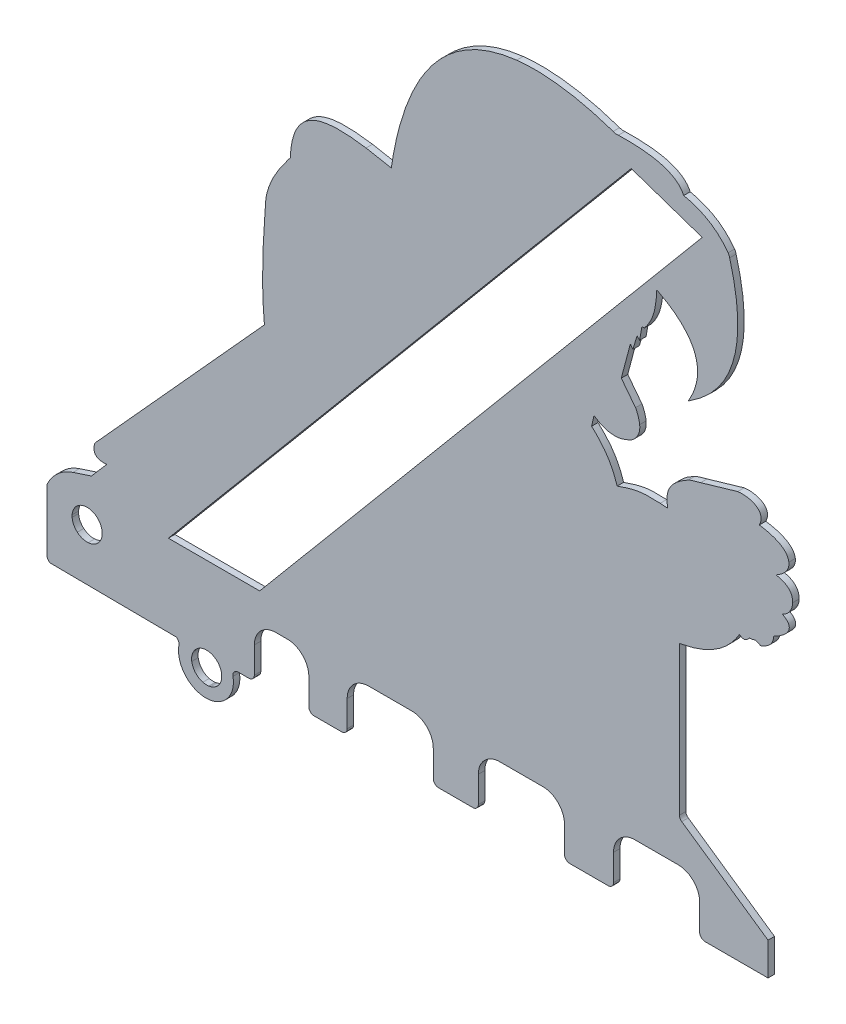
SolidWorks part; units mm, degrees
ref_plane "Plano frontal" through (0, 0, 0) normal (0, 0, 1) x (1, 0, 0)
ref_plane "Plano superior" through (0, 0, 0) normal (0, 1, 0) x (1, 0, 0)
ref_plane "Plano direito" through (0, 0, 0) normal (1, 0, 0) x (0, 0, -1)
sketch "Esboço1" plane through (0, 0, 0) normal (0, 0, 1) x (1, 0, 0)
  line L19 (-31.1212, 70.1729) -> (-31.7136, 66.5161)
  line L20 (-31.7136, 66.5161) -> (-38.8182, 67.8386)
  line L21 (-67.148, 39.828) -> (-67.3194, 37.296)
  line L22 (-67.4451, 10.3917) -> (-115.1674, -42.2747)
  line L23 (-115.1674, -42.2747) -> (-115.2355, -42.4873)
  line L24 (-111.8232, -45.8037) -> (-116.1591, -50.8302)
  line L25 (-116.1591, -50.8302) -> (-121.3469, -52.5308)
  line L26 (-128.6968, -59.2368) -> (-128.6968, -76.4218)
  line L27 (-127.7388, -77.831) -> (-92.2531, -78.1406)
  line L28 (-74.8085, -77.9727) -> (-71.8004, -77.9727)
  line L29 (-70.285, -76.4573) -> (-70.285, -69.0697)
  line L30 (-64.2237, -63.0084) -> (-61.0036, -63.0084)
  line L31 (-54.9422, -69.0697) -> (-54.9422, -76.4573)
  line L32 (-53.4269, -77.9727) -> (-45.6607, -77.9727)
  line L33 (-44.1454, -76.4573) -> (-44.1454, -69.0697)
  line L34 (-38.084, -63.0084) -> (-25.9613, -63.0084)
  line L35 (-19.9, -69.0697) -> (-19.9, -76.4573)
  line L36 (-18.3846, -77.9727) -> (-8.7243, -77.9727)
  line L37 (-7.209, -76.4573) -> (-7.209, -69.0697)
  line L38 (-1.1476, -63.0084) -> (10.9751, -63.0084)
  line L39 (17.0365, -69.0697) -> (17.0365, -76.4573)
  line L40 (18.5519, -77.9727) -> (29.3487, -77.9727)
  line L41 (30.864, -76.4573) -> (30.864, -69.0697)
  line L42 (36.9254, -63.0084) -> (49.0481, -63.0084)
  line L43 (55.1095, -69.0697) -> (55.1095, -76.4573)
  line L44 (56.6249, -77.9727) -> (74.9048, -77.9727)
  line L45 (76.4201, -76.4573) -> (76.4201, -70.9533)
  line L46 (75.7654, -69.7061) -> (50.0817, -51.9828)
  line L47 (49.427, -50.7356) -> (49.427, -8.8599)
  line L48 (69.1301, 2.3438) -> (69.5853, 2.3344)
  line L49 (65.824, 36.3827) -> (55.3959, 33.3376)
  line L50 (46.0183, 22.4541) -> (43.9835, 22.6052)
  line L51 (24.6909, 31.7377) -> (25.3594, 34.6947)
  line L52 (37.0566, 42.457) -> (33.0457, 47.6549)
  line L53 (33.0457, 47.6549) -> (35.6032, 57.2819)
  line L54 (35.6032, 57.2819) -> (36.3138, 56.2916)
  line L55 (36.3138, 56.2916) -> (37.4927, 60.2151)
  line L56 (37.4927, 60.2151) -> (38.2192, 59.4591)
  line L57 (38.2192, 59.4591) -> (38.84, 63.1265)
  line L58 (38.84, 63.1265) -> (39.5605, 63.1361)
  line L59 (51.9073, 51.5217) -> (52.346, 51.7973)
  line L164 (35.8473, 100.176) -> (-94.4917, -55.1466)
  line L165 (-68.768, -55.1466) -> (-94.4917, -55.1466)
  line L166 (-68.768, -55.1466) -> (55.8412, 93.357)
  line L167 (35.8473, 100.176) -> (55.8412, 93.357)
  arc A0 (-128.6531, -59.137) -> (-128.6968, -59.2368) centre (-117.1663, -64.2263) ccw
  arc A10 (27.7839, 36.7309) -> (28.2036, 38.047) centre (25.9306, 38.0468) ccw
  arc A27 (-113.127, -63.0084) -> (-113.1293, -62.9762) centre (-116.3703, -63.2239) ccw
  arc A28 (-121.5945, -63.0084) -> (-121.5923, -63.5991) centre (-117.3692, -63.2881) ccw
  arc A39 (-80.9411, -78.0866) -> (-81.1259, -77.9372) centre (-83.72, -81.3349) ccw
  arc A40 (-80.7705, -78.2408) -> (-80.9411, -78.0866) centre (-83.6897, -81.299) ccw
  arc A41 (-79.9492, -79.3267) -> (-80.7705, -78.2408) centre (-83.7019, -81.3115) ccw
  arc A42 (-79.7838, -79.6774) -> (-79.9492, -79.3267) centre (-83.7321, -81.3252) ccw
  arc A43 (-79.4971, -80.7287) -> (-79.7838, -79.6774) centre (-83.7037, -81.3112) ccw
  arc A44 (-79.6685, -82.6327) -> (-79.4971, -80.7287) centre (-83.7013, -81.31) ccw
  arc A45 (-82.507, -85.3818) -> (-81.3843, -84.8653) centre (-83.6993, -81.3119) ccw
  arc A46 (-82.8906, -85.4751) -> (-82.507, -85.3818) centre (-83.6947, -81.334) ccw
  arc A47 (-84.7848, -85.412) -> (-83.1187, -85.513) centre (-83.7001, -81.3113) ccw
  arc A48 (-86.2742, -77.9372) -> (-86.5757, -78.1902) centre (-83.7232, -81.2834) ccw
  arc A49 (-85.9707, -77.7258) -> (-86.2742, -77.9372) centre (-83.7208, -81.2796) ccw
  arc A50 (-85.0891, -77.3009) -> (-85.9707, -77.7258) centre (-83.7001, -81.31) ccw
  arc A51 (-84.2815, -77.1071) -> (-85.0891, -77.3009) centre (-83.698, -81.3186) ccw
  spline S27 degree 3 poles (32.2291, 106.4796) (31.2359, 106.4567) (31.6363, 106.3849) (30.7638, 106.6821) knots 0.019608 0.019608 0.019608 0.019608 0.029412 0.029412 0.029412 0.029412
  spline S28 degree 3 poles (30.7638, 106.6821) (22.1916, 109.6023) (12.6477, 111.4952) (3.5813, 110.463) knots 0.009804 0.009804 0.009804 0.009804 0.019608 0.019608 0.019608 0.019608
  spline S29 degree 3 poles (3.5813, 110.463) (-18.2288, 107.9799) (-27.5136, 89.9735) (-31.1212, 70.1729) knots 0 0 0 0 0.009804 0.009804 0.009804 0.009804
  spline S30 degree 3 poles (-38.8182, 67.8386) (-50.0724, 69.5332) (-59.3266, 68.7876) (-60.1044, 55.5309) knots 0.970588 0.970588 0.970588 0.970588 0.980392 0.980392 0.980392 0.980392
  spline S31 degree 3 poles (-60.1044, 55.5309) (-60.1598, 54.5873) (-60.0191, 54.9431) (-60.5508, 54.2708) knots 0.960784 0.960784 0.960784 0.960784 0.970588 0.970588 0.970588 0.970588
  spline S32 degree 3 poles (-60.5508, 54.2708) (-63.6828, 50.3105) (-67.0439, 45.0434) (-67.148, 39.828) knots 0.95098 0.95098 0.95098 0.95098 0.960784 0.960784 0.960784 0.960784
  spline S33 degree 3 poles (-67.3194, 37.296) (-68.0121, 28.366) (-68.2864, 19.322) (-67.4451, 10.3917) knots 0.931373 0.931373 0.931373 0.931373 0.941176 0.941176 0.941176 0.941176
  spline S34 degree 3 poles (-115.2355, -42.4873) (-116.0431, -45.1869) (-114.3851, -46.1186) (-111.8232, -45.8037) knots 0.901961 0.901961 0.901961 0.901961 0.911765 0.911765 0.911765 0.911765
  spline S35 degree 3 poles (-121.3469, -52.5308) (-124.5985, -53.5967) (-127.2605, -55.9937) (-128.6531, -59.137) knots 0.872549 0.872549 0.872549 0.872549 0.882353 0.882353 0.882353 0.882353
  spline S36 degree 3 poles (-128.6968, -76.4218) (-128.6966, -77.0433) (-128.3168, -77.6026) (-127.7388, -77.831) knots 0.843137 0.843137 0.843137 0.843137 0.852941 0.852941 0.852941 0.852941
  spline S37 degree 3 poles (-92.2531, -78.1406) (-91.9839, -78.2141) (-91.3744, -78.9137) (-91.5204, -79.7219) knots 0.823529 0.823529 0.823529 0.823529 0.833333 0.833333 0.833333 0.833333
  spline S38 degree 3 poles (-91.5204, -79.7219) (-92.2275, -83.6356) (-89.8311, -87.5281) (-85.8894, -88.5699) knots 0.813725 0.813725 0.813725 0.813725 0.823529 0.823529 0.823529 0.823529
  spline S39 degree 3 poles (-85.8894, -88.5699) (-80.4731, -90.0015) (-75.3167, -85.331) (-76.3007, -79.7516) knots 0.803922 0.803922 0.803922 0.803922 0.813725 0.813725 0.813725 0.813725
  spline S40 degree 3 poles (-76.3007, -79.7516) (-76.465, -78.8199) (-75.7455, -77.9727) (-74.8085, -77.9727) knots 0.794118 0.794118 0.794118 0.794118 0.803922 0.803922 0.803922 0.803922
  spline S41 degree 3 poles (-71.8004, -77.9727) (-70.9636, -77.9724) (-70.2848, -77.2943) (-70.285, -76.4573) knots 0.77451 0.77451 0.77451 0.77451 0.784314 0.784314 0.784314 0.784314
  spline S42 degree 3 poles (-70.285, -69.0697) (-70.2861, -65.7269) (-67.5662, -63.0094) (-64.2237, -63.0084) knots 0.754902 0.754902 0.754902 0.754902 0.764706 0.764706 0.764706 0.764706
  spline S43 degree 3 poles (-61.0036, -63.0084) (-57.6608, -63.0073) (-54.9432, -65.7272) (-54.9422, -69.0697) knots 0.735294 0.735294 0.735294 0.735294 0.745098 0.745098 0.745098 0.745098
  spline S44 degree 3 poles (-54.9422, -76.4573) (-54.9419, -77.2942) (-54.2638, -77.9729) (-53.4269, -77.9727) knots 0.715686 0.715686 0.715686 0.715686 0.72549 0.72549 0.72549 0.72549
  spline S45 degree 3 poles (-45.6607, -77.9727) (-44.8239, -77.9724) (-44.1451, -77.2943) (-44.1454, -76.4573) knots 0.696078 0.696078 0.696078 0.696078 0.705882 0.705882 0.705882 0.705882
  spline S46 degree 3 poles (-44.1454, -69.0697) (-44.1464, -65.7269) (-41.4266, -63.0094) (-38.084, -63.0084) knots 0.676471 0.676471 0.676471 0.676471 0.686275 0.686275 0.686275 0.686275
  spline S47 degree 3 poles (-25.9613, -63.0084) (-22.6186, -63.0073) (-19.901, -65.7271) (-19.9, -69.0697) knots 0.656863 0.656863 0.656863 0.656863 0.666667 0.666667 0.666667 0.666667
  spline S48 degree 3 poles (-19.9, -76.4573) (-19.8997, -77.2941) (-19.2216, -77.9729) (-18.3846, -77.9727) knots 0.637255 0.637255 0.637255 0.637255 0.647059 0.647059 0.647059 0.647059
  spline S49 degree 3 poles (-8.7243, -77.9727) (-7.8875, -77.9724) (-7.2087, -77.2942) (-7.209, -76.4573) knots 0.617647 0.617647 0.617647 0.617647 0.627451 0.627451 0.627451 0.627451
  spline S50 degree 3 poles (-7.209, -69.0697) (-7.21, -65.7269) (-4.4902, -63.0094) (-1.1476, -63.0084) knots 0.598039 0.598039 0.598039 0.598039 0.607843 0.607843 0.607843 0.607843
  spline S51 degree 3 poles (10.9751, -63.0084) (14.3179, -63.0073) (17.0355, -65.7271) (17.0365, -69.0697) knots 0.578431 0.578431 0.578431 0.578431 0.588235 0.588235 0.588235 0.588235
  spline S52 degree 3 poles (17.0365, -76.4573) (17.0368, -77.2943) (17.7149, -77.9729) (18.5519, -77.9727) knots 0.558824 0.558824 0.558824 0.558824 0.568627 0.568627 0.568627 0.568627
  spline S53 degree 3 poles (29.3487, -77.9727) (30.1855, -77.9724) (30.8643, -77.2942) (30.864, -76.4573) knots 0.539216 0.539216 0.539216 0.539216 0.54902 0.54902 0.54902 0.54902
  spline S54 degree 3 poles (30.864, -69.0697) (30.863, -65.7269) (33.5828, -63.0094) (36.9254, -63.0084) knots 0.519608 0.519608 0.519608 0.519608 0.529412 0.529412 0.529412 0.529412
  spline S55 degree 3 poles (49.0481, -63.0084) (52.3909, -63.0073) (55.1085, -65.7271) (55.1095, -69.0697) knots 0.5 0.5 0.5 0.5 0.509804 0.509804 0.509804 0.509804
  spline S56 degree 3 poles (55.1095, -76.4573) (55.1098, -77.2943) (55.7879, -77.9729) (56.6249, -77.9727) knots 0.480392 0.480392 0.480392 0.480392 0.490196 0.490196 0.490196 0.490196
  spline S57 degree 3 poles (74.9048, -77.9727) (75.7415, -77.9724) (76.4204, -77.2942) (76.4201, -76.4573) knots 0.460784 0.460784 0.460784 0.460784 0.470588 0.470588 0.470588 0.470588
  spline S58 degree 3 poles (76.4201, -70.9533) (76.42, -70.4554) (76.1753, -69.9888) (75.7654, -69.7061) knots 0.441176 0.441176 0.441176 0.441176 0.45098 0.45098 0.45098 0.45098
  spline S59 degree 3 poles (50.0817, -51.9828) (49.6715, -51.6999) (49.4271, -51.2338) (49.427, -50.7356) knots 0.421569 0.421569 0.421569 0.421569 0.431373 0.431373 0.431373 0.431373
  spline S60 degree 3 poles (49.427, -8.8599) (56.518, -7.5985) (62.5556, -4.5909) (66.3065, 1.7714) knots 0.401961 0.401961 0.401961 0.401961 0.411765 0.411765 0.411765 0.411765
  spline S61 degree 3 poles (66.3065, 1.7714) (67.5954, 0.8929) (68.2878, 1.221) (69.1301, 2.3438) knots 0.392157 0.392157 0.392157 0.392157 0.401961 0.401961 0.401961 0.401961
  spline S62 degree 3 poles (69.5853, 2.3344) (70.7655, 2.486) (70.6179, 2.937) (71.7993, 2.2586) knots 0.372549 0.372549 0.372549 0.372549 0.382353 0.382353 0.382353 0.382353
  spline S63 degree 3 poles (71.7993, 2.2586) (72.2728, 1.9867) (72.2753, 2.016) (72.6299, 2.1627) knots 0.362745 0.362745 0.362745 0.362745 0.372549 0.372549 0.372549 0.372549
  spline S64 degree 3 poles (72.6299, 2.1627) (74.5774, 2.9684) (75.7834, 4.0271) (75.9888, 6.1776) knots 0.352941 0.352941 0.352941 0.352941 0.362745 0.362745 0.362745 0.362745
  spline S65 degree 3 poles (75.9888, 6.1776) (78.6869, 7.5241) (82.8418, 10.4875) (78.379, 12.791) knots 0.343137 0.343137 0.343137 0.343137 0.352941 0.352941 0.352941 0.352941
  spline S66 degree 3 poles (78.379, 12.791) (80.1225, 13.4928) (81.2558, 15.1731) (81.3022, 17.0125) knots 0.333333 0.333333 0.333333 0.333333 0.343137 0.343137 0.343137 0.343137
  spline S67 degree 3 poles (81.3022, 17.0125) (81.3725, 19.7981) (79.1036, 21.1153) (76.5701, 21.4419) knots 0.323529 0.323529 0.323529 0.323529 0.333333 0.333333 0.333333 0.333333
  spline S68 degree 3 poles (76.5701, 21.4419) (78.335, 22.3864) (80.5268, 24.099) (80.2302, 26.3716) knots 0.313725 0.313725 0.313725 0.313725 0.323529 0.323529 0.323529 0.323529
  spline S69 degree 3 poles (80.2302, 26.3716) (79.7885, 29.7559) (74.6119, 30.9063) (71.9178, 31.2769) knots 0.303922 0.303922 0.303922 0.303922 0.313725 0.313725 0.313725 0.313725
  spline S70 degree 3 poles (71.9178, 31.2769) (74.035, 35.6067) (68.7506, 36.832) (65.824, 36.3827) knots 0.294118 0.294118 0.294118 0.294118 0.303922 0.303922 0.303922 0.303922
  spline S71 degree 3 poles (55.3959, 33.3376) (54.6256, 33.1101) (52.5995, 32.5941) (51.9317, 32.2413) knots 0.27451 0.27451 0.27451 0.27451 0.284314 0.284314 0.284314 0.284314
  spline S72 degree 3 poles (51.9317, 32.2413) (49.454, 30.9325) (46.5998, 28.9058) (46.0348, 25.9653) knots 0.264706 0.264706 0.264706 0.264706 0.27451 0.27451 0.27451 0.27451
  spline S73 degree 3 poles (46.0348, 25.9653) (45.8826, 25.1729) (46.004, 23.1475) (46.0183, 22.4541) knots 0.254902 0.254902 0.254902 0.254902 0.264706 0.264706 0.264706 0.264706
  spline S74 degree 3 poles (43.9835, 22.6052) (38.6527, 22.9148) (36.7693, 22.456) (31.8872, 20.7468) knots 0.235294 0.235294 0.235294 0.235294 0.245098 0.245098 0.245098 0.245098
  spline S75 degree 3 poles (31.8872, 20.7468) (30.4706, 25.3641) (28.2254, 28.491) (24.6909, 31.7377) knots 0.22549 0.22549 0.22549 0.22549 0.235294 0.235294 0.235294 0.235294
  spline S76 degree 3 poles (25.3594, 34.6947) (27.5181, 33.2153) (29.6478, 32.4049) (32.28, 32.7433) knots 0.205882 0.205882 0.205882 0.205882 0.215686 0.215686 0.215686 0.215686
  spline S77 degree 3 poles (32.28, 32.7433) (33.4761, 32.8971) (35.5829, 33.6758) (36.4141, 34.3997) knots 0.196078 0.196078 0.196078 0.196078 0.205882 0.205882 0.205882 0.205882
  spline S78 degree 3 poles (36.4141, 34.3997) (37.7762, 35.586) (38.4112, 37.0942) (38.2242, 38.9061) knots 0.186275 0.186275 0.186275 0.186275 0.196078 0.196078 0.196078 0.196078
  spline S79 degree 3 poles (38.2242, 38.9061) (38.1205, 39.9111) (37.5493, 41.6684) (37.0566, 42.457) knots 0.176471 0.176471 0.176471 0.176471 0.186275 0.186275 0.186275 0.186275
  spline S80 degree 3 poles (39.5605, 63.1361) (42.3259, 66.4566) (42.8665, 70.0045) (43.0408, 74.1907) knots 0.098039 0.098039 0.098039 0.098039 0.107843 0.107843 0.107843 0.107843
  spline S81 degree 3 poles (43.0408, 74.1907) (45.4622, 72.9393) (47.6991, 71.5807) (49.7205, 69.7333) knots 0.088235 0.088235 0.088235 0.088235 0.098039 0.098039 0.098039 0.098039
  spline S82 degree 3 poles (49.7205, 69.7333) (55.6006, 64.3593) (55.8041, 58.2068) (51.9073, 51.5217) knots 0.078431 0.078431 0.078431 0.078431 0.088235 0.088235 0.088235 0.088235
  spline S83 degree 3 poles (52.346, 51.7973) (67.1516, 61.2493) (67.8456, 76.7151) (63.5644, 92.2344) knots 0.058824 0.058824 0.058824 0.058824 0.068627 0.068627 0.068627 0.068627
  spline S84 degree 3 poles (63.5644, 92.2344) (63.3857, 92.8822) (63.4709, 92.7532) (63.1176, 93.2443) knots 0.04902 0.04902 0.04902 0.04902 0.058824 0.058824 0.058824 0.058824
  spline S85 degree 3 poles (63.1176, 93.2443) (59.9959, 97.5833) (55.7711, 99.8804) (50.6198, 100.9683) knots 0.039216 0.039216 0.039216 0.039216 0.04902 0.04902 0.04902 0.04902
  spline S86 degree 3 poles (50.6198, 100.9683) (48.1501, 106.5914) (37.3051, 106.5967) (32.2291, 106.4796) knots 0.029412 0.029412 0.029412 0.029412 0.039216 0.039216 0.039216 0.039216
  spline S138 degree 3 poles (27.5364, 39.6548) (27.1096, 40.0811) (26.5338, 40.3204) (25.9306, 40.32) knots 0.333333 0.333333 0.333333 0.333333 0.416667 0.416667 0.416667 0.416667
  spline S139 degree 3 poles (28.2036, 38.047) (28.2032, 38.6502) (27.9632, 39.2286) (27.5364, 39.6548) knots 0.25 0.25 0.25 0.25 0.333333 0.333333 0.333333 0.333333
  spline S140 degree 3 poles (25.9306, 35.774) (26.6671, 35.7741) (27.3575, 36.1303) (27.7839, 36.7309) knots 0.083333 0.083333 0.083333 0.083333 0.166667 0.166667 0.166667 0.166667
  spline S198 degree 3 poles (-81.1259, -77.9372) (-82.0254, -77.2509) (-83.1608, -76.952) (-84.2815, -77.1071) knots 0.722222 0.722222 0.722222 0.722222 0.777778 0.777778 0.777778 0.777778
  spline S199 degree 3 poles (-81.3843, -84.8653) (-80.5748, -84.3379) (-79.9696, -83.5507) (-79.6685, -82.6327) knots 0.333333 0.333333 0.333333 0.333333 0.388889 0.388889 0.388889 0.388889
  spline S200 degree 3 poles (-83.1187, -85.513) (-83.0423, -85.5025) (-82.9663, -85.4898) (-82.8906, -85.4751) knots 0.166667 0.166667 0.166667 0.166667 0.222222 0.222222 0.222222 0.222222
  spline S201 degree 3 poles (-87.903, -81.8915) (-87.668, -83.587) (-86.4398, -84.9749) (-84.7848, -85.412) knots 0.055556 0.055556 0.055556 0.055556 0.111111 0.111111 0.111111 0.111111
  spline S202 degree 3 poles (-86.5757, -78.1902) (-87.5978, -79.1326) (-88.0938, -80.5144) (-87.903, -81.8915) knots 0 0 0 0 0.055556 0.055556 0.055556 0.055556
  spline S203 degree 3 poles (-113.1293, -62.9762) (-113.2126, -61.8532) (-113.7387, -60.8094) (-114.5917, -60.0744) knots 0.625 0.625 0.625 0.625 0.75 0.75 0.75 0.75
  spline S204 degree 3 poles (-117.0493, -67.5192) (-114.7235, -67.3465) (-112.9721, -65.3354) (-113.127, -63.0084) knots 0.375 0.375 0.375 0.375 0.5 0.5 0.5 0.5
  spline S205 degree 3 poles (-120.1299, -66.501) (-119.2769, -67.236) (-118.1722, -67.6025) (-117.0493, -67.5192) knots 0.25 0.25 0.25 0.25 0.375 0.375 0.375 0.375
  spline S206 degree 3 poles (-121.5923, -63.5991) (-121.5089, -64.7221) (-120.9829, -65.7659) (-120.1299, -66.501) knots 0.125 0.125 0.125 0.125 0.25 0.25 0.25 0.25
  spline S207 degree 3 poles (-117.6723, -59.0561) (-119.7833, -59.2126) (-121.4562, -60.8961) (-121.5945, -63.0084) knots 0.875 0.875 0.875 0.875 1 1 1 1
  spline S208 degree 3 poles (-114.5917, -60.0744) (-115.4446, -59.3393) (-116.5494, -58.9728) (-117.6723, -59.0561) knots 0.75 0.75 0.75 0.75 0.875 0.875 0.875 0.875
extrude "Ressalto-extrusão1" add sketch "Esboço1" along normal blind 6 contours S29 L19 L20 S30 S31 S32 L21 S33 L22 L23 S34 L24 L25 S35 A0 L26 S36 L27 S37 S38 S39 S40 L28 S41 L29 S42 L30 S43 L31 S44 L32 S45 L33 S46 L34 S47 L35 S48 L36 S49 L37 S50 L38 S51 L39 S52 L40 S53 L41 S54 L42 S55 L43 S56 L44 S57 L45 S58 L46 S59 L47 S60 S61 L48 S62 S63 S64 S65 S66 S67 S68 S69 S70 L49 S71 S72 S73 L50 S74 S75 L51 S76 S77 S78 S79 L52 L53 L54 L55 L56 L57 L58 S80 S81 S82 L59 S83 S84 S85 S86 S27 S28 | L164 L165 L166 L167 | S204 A27 S203 S208 S207 A28 S206 S205 | S198 A51 A50 A49 A48 S202 S201 A47 S200 A46 A45 S199 A44 A43 A42 A41 A40 A39
scale "Escala3" scale about origin uniform scaling yes scale factor 3.299524
sketch "Esboço4" plane through (0, 0, 19.7971) normal (0, 0, 1) x (1, 0, 0)
  line L41 (-102.6853, 231.537) -> (-104.6399, 219.4713)
  line L42 (-104.6399, 219.4713) -> (-128.0817, 223.8349)
  line L43 (-221.5566, 131.4133) -> (-222.1221, 123.0589)
  line L44 (-222.5369, 34.2875) -> (-379.9977, -139.4865)
  line L45 (-379.9977, -139.4865) -> (-380.2224, -140.188)
  line L46 (-368.9635, -151.1306) -> (-383.2699, -167.7156)
  line L47 (-383.2699, -167.7156) -> (-400.3872, -173.3268)
  line L48 (-424.6383, -195.4534) -> (-424.6383, -252.1557)
  line L49 (-421.4774, -256.8054) -> (-304.3915, -257.8269)
  line L50 (-246.8326, -257.2729) -> (-236.9073, -257.2729)
  line L51 (-231.9072, -252.2728) -> (-231.9072, -227.8973)
  line L52 (-211.9078, -207.8979) -> (-201.283, -207.8979)
  line L53 (-181.2833, -227.8973) -> (-181.2833, -252.2728)
  line L54 (-176.2835, -257.2729) -> (-150.6587, -257.2729)
  line L55 (-145.659, -252.2728) -> (-145.659, -227.8973)
  line L56 (-125.6592, -207.8979) -> (-85.6601, -207.8979)
  line L57 (-65.6607, -227.8973) -> (-65.6607, -252.2728)
  line L58 (-60.6606, -257.2729) -> (-28.7862, -257.2729)
  line L59 (-23.7864, -252.2728) -> (-23.7864, -227.8973)
  line L60 (-3.7867, -207.8979) -> (36.2124, -207.8979)
  line L61 (56.2122, -227.8973) -> (56.2122, -252.2728)
  line L62 (61.2123, -257.2729) -> (96.8366, -257.2729)
  line L63 (101.8363, -252.2728) -> (101.8363, -227.8973)
  line L64 (121.8361, -207.8979) -> (161.8352, -207.8979)
  line L65 (181.8349, -227.8973) -> (181.8349, -252.2728)
  line L66 (186.835, -257.2729) -> (247.15, -257.2729)
  line L67 (252.1498, -252.2728) -> (252.1498, -234.1123)
  line L68 (249.9896, -229.9971) -> (165.2456, -171.5186)
  line L69 (163.0854, -167.4035) -> (163.0854, -29.2336)
  line L70 (228.0962, 7.7333) -> (229.5982, 7.7022)
  line L71 (217.1877, 120.0454) -> (182.7799, 109.998)
  line L72 (151.8383, 74.0877) -> (145.1244, 74.5862)
  line L73 (81.468, 104.7191) -> (83.6738, 114.4758)
  line L74 (122.269, 140.0877) -> (109.0349, 157.2383)
  line L75 (109.0349, 157.2383) -> (117.4734, 189.0028)
  line L76 (117.4734, 189.0028) -> (119.8181, 185.7353)
  line L77 (119.8181, 185.7353) -> (123.7079, 198.681)
  line L78 (123.7079, 198.681) -> (126.105, 196.1866)
  line L79 (126.105, 196.1866) -> (128.1533, 208.2872)
  line L80 (128.1533, 208.2872) -> (130.5306, 208.3189)
  line L81 (171.2692, 169.9969) -> (172.7167, 170.9063)
  line L82 (-102.6853, 231.537) -> (-104.6399, 219.4713)
  line L83 (-104.6399, 219.4713) -> (-128.0817, 223.8349)
  line L84 (-221.5566, 131.4133) -> (-222.1221, 123.0589)
  line L85 (-222.5369, 34.2875) -> (-379.9977, -139.4865)
  line L86 (-379.9977, -139.4865) -> (-380.2224, -140.188)
  line L87 (-368.9635, -151.1306) -> (-383.2699, -167.7156)
  line L88 (-383.2699, -167.7156) -> (-400.3872, -173.3268)
  line L89 (-424.6383, -195.4534) -> (-424.6383, -252.1557)
  line L90 (-421.4774, -256.8054) -> (-304.3915, -257.8269)
  line L91 (-246.8326, -257.2729) -> (-236.9073, -257.2729)
  line L92 (-231.9072, -252.2728) -> (-231.9072, -227.8973)
  line L93 (-211.9078, -207.8979) -> (-201.283, -207.8979)
  line L94 (-181.2833, -227.8973) -> (-181.2833, -252.2728)
  line L95 (-176.2835, -257.2729) -> (-150.6587, -257.2729)
  line L96 (-145.659, -252.2728) -> (-145.659, -227.8973)
  line L97 (-125.6592, -207.8979) -> (-85.6601, -207.8979)
  line L98 (-65.6607, -227.8973) -> (-65.6607, -252.2728)
  line L99 (-60.6606, -257.2729) -> (-28.7862, -257.2729)
  line L100 (-23.7864, -252.2728) -> (-23.7864, -227.8973)
  line L101 (-3.7867, -207.8979) -> (36.2124, -207.8979)
  line L102 (56.2122, -227.8973) -> (56.2122, -252.2728)
  line L103 (61.2123, -257.2729) -> (96.8366, -257.2729)
  line L104 (101.8363, -252.2728) -> (101.8363, -227.8973)
  line L105 (121.8361, -207.8979) -> (161.8352, -207.8979)
  line L106 (181.8349, -227.8973) -> (181.8349, -252.2728)
  line L107 (186.835, -257.2729) -> (247.15, -257.2729)
  line L108 (252.1498, -252.2728) -> (252.1498, -234.1123)
  line L109 (249.9896, -229.9971) -> (165.2456, -171.5186)
  line L110 (163.0854, -167.4035) -> (163.0854, -29.2336)
  line L111 (228.0962, 7.7333) -> (229.5982, 7.7022)
  line L112 (217.1877, 120.0454) -> (182.7799, 109.998)
  line L113 (151.8383, 74.0877) -> (145.1244, 74.5862)
  line L114 (81.468, 104.7191) -> (83.6738, 114.4758)
  line L115 (122.269, 140.0877) -> (109.0349, 157.2383)
  line L116 (109.0349, 157.2383) -> (117.4734, 189.0028)
  line L117 (117.4734, 189.0028) -> (119.8181, 185.7353)
  line L118 (119.8181, 185.7353) -> (123.7079, 198.681)
  line L119 (123.7079, 198.681) -> (126.105, 196.1866)
  line L120 (126.105, 196.1866) -> (128.1533, 208.2872)
  line L121 (128.1533, 208.2872) -> (130.5306, 208.3189)
  line L122 (171.2692, 169.9969) -> (172.7167, 170.9063)
  arc A1 (-424.4941, -195.1241) -> (-424.6383, -195.4534) centre (-386.5929, -211.9163) ccw
  arc A2 (-424.4941, -195.1241) -> (-424.6383, -195.4534) centre (-386.5929, -211.9163) ccw
  spline S60 degree 3 poles (-2749.7739, 3156.1075) (3311.9083, -3117.4694) (-2516.8081, 4110.4113) (1302.0473, -3365.3013) knots -0.073008 -0.073008 -0.073008 -0.073008 0.088903 0.088903 0.088903 0.088903 only from (101.5057, 352) to (11.8164, 364.4751)
  spline S61 degree 3 poles (2683.5587, -2574.6031) (-2399.3142, 4426.4123) (1717.2504, -4445.8715) (-1510.3459, 3975.2212) knots -0.031205 -0.031205 -0.031205 -0.031205 0.057158 0.057158 0.057158 0.057158 only from (11.8164, 364.4751) to (-102.6853, 231.537)
  spline S62 degree 3 poles (-1820.9177, 3816.7963) (2422.5595, -3496.4286) (-2666.0809, 3905.2396) (1766.8331, -3295.9443) knots 0.921018 0.921018 0.921018 0.921018 1.015048 1.015048 1.015048 1.015048 only from (-128.0817, 223.8349) to (-198.3161, 183.2254)
  spline S63 degree 3 poles (1044.5155, 3984.6182) (-1535.9311, -3561.3649) (1242.2589, 3884.2318) (-1751.3161, -3507.0429) knots 0.888803 0.888803 0.888803 0.888803 1.042913 1.042913 1.042913 1.042913 only from (-198.3161, 183.2254) to (-199.789, 179.0676)
  spline S64 degree 3 poles (-3783.4688, -1596.5461) (3767.8418, 1989.9939) (-4283.0651, -1291.9556) (3691.2059, 882.5004) knots 0.883869 0.883869 0.883869 0.883869 1.021217 1.021217 1.021217 1.021217 only from (-199.789, 179.0676) to (-221.5566, 131.4133)
  spline S65 degree 3 poles (-4087.7326, -447.5701) (3817.027, 1944.8626) (-4265.3711, -1362.6264) (3695.0979, 90.7153) knots 0.807766 0.807766 0.807766 0.807766 1.043623 1.043623 1.043623 1.043623 only from (-222.1221, 123.0589) to (-222.5369, 34.2875)
  spline S66 degree 3 poles (3147.5175, 1733.4205) (-4370.2257, -1776.6623) (3838.1303, 1018.1238) (-4324.6269, -596.3641) knots 0.829058 0.829058 0.829058 0.829058 1.009445 1.009445 1.009445 1.009445 only from (-380.2224, -140.188) to (-368.9635, -151.1306)
  spline S67 degree 3 poles (-2028.2981, -3768.5073) (2294.3809, 2881.4113) (-3846.6982, -2401.0579) (3373.4408, 879.5925) knots 0.769396 0.769396 0.769396 0.769396 0.984905 0.984905 0.984905 0.984905 only from (-400.3872, -173.3268) to (-424.4941, -195.1241)
  spline S68 degree 3 poles (2446.9824, -3020.4042) (-2902.9167, 2921.8167) (1595.7175, -3741.9804) (-1915.6704, 3441.3125) knots 0.695962 0.695962 0.695962 0.695962 1.00004 1.00004 1.00004 1.00004 only from (-424.6383, -252.1557) to (-421.4774, -256.8054)
  spline S69 degree 3 poles (3129.6994, -2305.0833) (-3897.5231, 1605.2935) (3408.4031, -1870.424) (-4084.4806, 1025.5563) knots 0.729872 0.729872 0.729872 0.729872 0.926417 0.926417 0.926417 0.926417 only from (-304.3915, -257.8269) to (-301.9739, -263.0445)
  spline S70 degree 3 poles (2708.7064, -2844.0972) (-2662.7419, 3047.0457) (1248.3099, -4055.9187) (-859.3025, 3632.0468) knots 0.747701 0.747701 0.747701 0.747701 0.888722 0.888722 0.888722 0.888722 only from (-301.9739, -263.0445) to (-283.3943, -292.2387)
  spline S71 degree 3 poles (1632.4153, 3184.0656) (-3012.706, -3317.1759) (3087.8072, 2070.0129) (-3937.8853, -1736.1197) knots 0.7562 0.7562 0.7562 0.7562 0.861253 0.861253 0.861253 0.861253 only from (-283.3943, -292.2387) to (-251.7561, -263.1425)
  spline S72 degree 3 poles (2923.4509, 2152.2992) (-3100.1342, -3113.3833) (2195.262, 2948.0678) (-2213.5904, -3728.2094) knots 0.695083 0.695083 0.695083 0.695083 0.903177 0.903177 0.903177 0.903177 only from (-251.7561, -263.1425) to (-246.8326, -257.2729)
  spline S73 degree 3 poles (1954.8505, 3075.9158) (-2891.3634, -3287.1157) (2808.6421, 2389.8367) (-3573.7385, -2430.6231) knots 0.663651 0.663651 0.663651 0.663651 0.895136 0.895136 0.895136 0.895136 only from (-236.9073, -257.2729) to (-231.9072, -252.2728)
  spline S74 degree 3 poles (3333.9041, 1521.4781) (-3396.7779, -2769.2937) (2340.4685, 2948.1086) (-1973.0672, -3767.7596) knots 0.687191 0.687191 0.687191 0.687191 0.832447 0.832447 0.832447 0.832447 only from (-231.9072, -227.8973) to (-211.9078, -207.8979)
  spline S75 degree 3 poles (1548.2978, -3773.6163) (-2742.8576, 2956.8596) (2974.859, -2780.1506) (-3741.229, 1533.1459) knots 0.667584 0.667584 0.667584 0.667584 0.812838 0.812838 0.812838 0.812838 only from (-201.283, -207.8979) to (-181.2833, -227.8973)
  spline S76 degree 3 poles (3152.7041, -2442.5799) (-3212.1162, 2400.935) (2466.9718, -3296.8243) (-2355.8841, 3083.8437) knots 0.604824 0.604824 0.604824 0.604824 0.836323 0.836323 0.836323 0.836323 only from (-181.2833, -252.2728) to (-176.2835, -257.2729)
  spline S77 degree 3 poles (2041.3321, 3075.5955) (-2805.331, -3286.7787) (2895.0859, 2389.4945) (-3487.6637, -2430.2902) knots 0.585224 0.585224 0.585224 0.585224 0.8167 0.8167 0.8167 0.8167 only from (-150.6587, -257.2729) to (-145.659, -252.2728)
  spline S78 degree 3 poles (3419.9926, 1521.7181) (-3310.2665, -2769.5448) (2426.3621, 2948.3349) (-1886.3963, -3767.9378) knots 0.608757 0.608757 0.608757 0.608757 0.754017 0.754017 0.754017 0.754017 only from (-145.659, -227.8973) to (-125.6592, -207.8979)
  spline S79 degree 3 poles (1664.2207, -3773.4582) (-2627.5074, 2956.6007) (3090.6991, -2779.8058) (-3625.7529, 1532.7422) knots 0.589151 0.589151 0.589151 0.589151 0.734407 0.734407 0.734407 0.734407 only from (-85.6601, -207.8979) to (-65.6607, -227.8973)
  spline S80 degree 3 poles (3267.5281, -2444.0307) (-3095.5034, 2402.1832) (2581.449, -3297.8222) (-2239.0109, 3084.5584) knots 0.526397 0.526397 0.526397 0.526397 0.757882 0.757882 0.757882 0.757882 only from (-65.6607, -252.2728) to (-60.6606, -257.2729)
  spline S81 degree 3 poles (2162.4532, 3076.1661) (-2682.6959, -3287.5707) (3016.2208, 2390.4914) (-3365.1064, -2431.4665) knots 0.506805 0.506805 0.506805 0.506805 0.73826 0.73826 0.73826 0.73826 only from (-28.7862, -257.2729) to (-23.7864, -252.2728)
  spline S82 degree 3 poles (3541.8651, 1521.7181) (-3188.3939, -2769.5448) (2548.2346, 2948.3349) (-1764.5238, -3767.9378) knots 0.530325 0.530325 0.530325 0.530325 0.675585 0.675585 0.675585 0.675585 only from (-23.7864, -227.8973) to (-3.7867, -207.8979)
  spline S83 degree 3 poles (1785.9601, -3773.5046) (-2505.5376, 2956.6573) (3212.5142, -2779.8672) (-3503.8617, 1532.8003) knots 0.510719 0.510719 0.510719 0.510719 0.655976 0.655976 0.655976 0.655976 only from (36.2124, -207.8979) to (56.2122, -227.8973)
  spline S84 degree 3 poles (3390.843, -2441.7366) (-2975.2096, 2400.286) (2704.9732, -3296.3821) (-2118.7775, 3083.6144) knots 0.447948 0.447948 0.447948 0.447948 0.679476 0.679476 0.679476 0.679476 only from (56.2122, -252.2728) to (61.2123, -257.2729)
  spline S85 degree 3 poles (2288.076, 3076.1661) (-2557.0732, -3287.5707) (3141.8436, 2390.4914) (-3239.4837, -2431.4665) knots 0.428373 0.428373 0.428373 0.428373 0.659829 0.659829 0.659829 0.659829 only from (96.8366, -257.2729) to (101.8363, -252.2728)
  spline S86 degree 3 poles (3667.4879, 1521.7181) (-3062.7712, -2769.5448) (2673.8574, 2948.3349) (-1638.901, -3767.9378) knots 0.451894 0.451894 0.451894 0.451894 0.597154 0.597154 0.597154 0.597154 only from (101.8363, -227.8973) to (121.8361, -207.8979)
  spline S87 degree 3 poles (1911.5829, -3773.5046) (-2379.9149, 2956.6573) (3338.137, -2779.8672) (-3378.2389, 1532.8003) knots 0.432288 0.432288 0.432288 0.432288 0.577545 0.577545 0.577545 0.577545 only from (161.8352, -207.8979) to (181.8349, -227.8973)
  spline S88 degree 3 poles (3516.4658, -2441.7366) (-2849.5868, 2400.286) (2830.5959, -3296.3821) (-1993.1548, 3083.6144) knots 0.369516 0.369516 0.369516 0.369516 0.601045 0.601045 0.601045 0.601045 only from (181.8349, -252.2728) to (186.835, -257.2729)
  spline S89 degree 3 poles (2439.4676, 3075.3568) (-2407.6434, -3286.7148) (3292.821, 2389.6187) (-3089.5987, -2430.6152) knots 0.349952 0.349952 0.349952 0.349952 0.581384 0.581384 0.581384 0.581384 only from (247.15, -257.2729) to (252.1498, -252.2728)
  spline S90 degree 3 poles (-2292.6423, 2836.9047) (2355.0779, -3667.6995) (-1354.8562, 3462.6641) (1304.6827, -4076.2814) knots 0.258247 0.258247 0.258247 0.258247 0.633809 0.633809 0.633809 0.633809 only from (252.1498, -234.1123) to (249.9896, -229.9971)
  spline S91 degree 3 poles (-880.9579, 3676.9839) (1765.4741, -3865.1648) (-1939.0124, 3265.581) (2710.7334, -3235.8525) knots 0.238126 0.238126 0.238126 0.238126 0.61493 0.61493 0.61493 0.61493 only from (165.2456, -171.5186) to (163.0854, -167.4035)
  spline S92 degree 3 poles (2242.5846, -3404.7053) (-2877.8143, 3460.7668) (2936.0989, -3562.6992) (-1745.4764, 3474.1661) knots 0.306556 0.306556 0.306556 0.306556 0.477125 0.477125 0.477125 0.477125 only from (163.0854, -29.2336) to (218.7797, 5.8446)
  spline S93 degree 3 poles (-2851.9939, 2563.2176) (3437.4506, -2189.6476) (-3242.09, 1643.0748) (4107.2857, -837.3766) knots 0.295373 0.295373 0.295373 0.295373 0.513161 0.513161 0.513161 0.513161 only from (218.7797, 5.8446) to (228.0962, 7.7333)
  spline S94 degree 3 poles (-3391.534, 1704.4226) (3745.6788, -1816.7862) (-3219.3716, 1949.5706) (3675.9749, -2034.5411) knots 0.304665 0.304665 0.304665 0.304665 0.448984 0.448984 0.448984 0.448984 only from (229.5982, 7.7022) to (236.9033, 7.4521)
  spline S95 degree 3 poles (-3609.1398, 1103.3251) (4089.9996, -938.0967) (-3646.7986, 795.3134) (4188.8811, -620.6907) knots 0.25846 0.25846 0.25846 0.25846 0.479222 0.479222 0.479222 0.479222 only from (236.9033, 7.4521) to (239.6439, 7.1357)
  spline S96 degree 3 poles (346.4558, -3955.5636) (-763.8144, 3754.7132) (1726.2019, -3647.5991) (-1396.9269, 3664.6957) knots 0.240262 0.240262 0.240262 0.240262 0.456817 0.456817 0.456817 0.456817 only from (239.6439, 7.1357) to (250.7267, 20.383)
  spline S97 degree 3 poles (4088.8626, 1144.4382) (-3808.8347, -1018.8502) (4361.1807, 865.9235) (-3701.7523, -501.0716) knots 0.29625 0.29625 0.29625 0.29625 0.393356 0.393356 0.393356 0.393356 only from (250.7267, 20.383) to (258.6132, 42.204)
  spline S98 degree 3 poles (1146.9521, 3917.773) (-1425.4716, -3644.823) (2640.7338, 3345.3929) (-2663.2484, -2629.1467) knots 0.232678 0.232678 0.232678 0.232678 0.445143 0.445143 0.445143 0.445143 only from (258.6132, 42.204) to (268.2584, 56.133)
  spline S99 degree 3 poles (-3424.6243, -1461.062) (4305.0263, 1208.5434) (-3917.3976, -659.1935) (4234.8582, 380.8846) knots 0.253417 0.253417 0.253417 0.253417 0.417901 0.417901 0.417901 0.417901 only from (268.2584, 56.133) to (252.6447, 70.7479)
  spline S100 degree 3 poles (4203.382, 689.595) (-3884.9605, -387.071) (4406.8342, 256.9331) (-3725.4384, 279.977) knots 0.241475 0.241475 0.241475 0.241475 0.389045 0.389045 0.389045 0.389045 only from (252.6447, 70.7479) to (264.7213, 87.0136)
  spline S101 degree 3 poles (-3535.8217, -1143.6395) (4347.2455, 1026.3048) (-3911.7396, -575.7189) (4205.3416, 601.7616) knots 0.256361 0.256361 0.256361 0.256361 0.365128 0.365128 0.365128 0.365128 only from (264.7213, 87.0136) to (237.2943, 103.1987)
  spline S102 degree 3 poles (-3606.269, -986.6222) (4338.0012, 877.5157) (-3942.705, -308.3943) (4212.1768, 240.9156) knots 0.252619 0.252619 0.252619 0.252619 0.351122 0.351122 0.351122 0.351122 only from (237.2943, 103.1987) to (217.1877, 120.0454)
  spline S103 degree 3 poles (-3753.3855, -600.8869) (4253.1191, 831.1412) (-3903.4573, -586.6571) (4121.5525, 734.6727) knots 0.203106 0.203106 0.203106 0.203106 0.355421 0.355421 0.355421 0.355421 only from (182.7799, 109.998) to (171.3497, 106.3808)
  spline S104 degree 3 poles (-3827.9932, 79.3495) (4387.9049, -14.0608) (-4013.578, 518.6994) (4054.6544, -753.9121) knots 0.189513 0.189513 0.189513 0.189513 0.341988 0.341988 0.341988 0.341988 only from (171.3497, 106.3808) to (151.8928, 85.673)
  spline S105 degree 3 poles (805.4699, -3860.3131) (-468.8011, 4168.6251) (736.2986, -4014.0848) (-394.7143, 4036.3035) knots 0.182946 0.182946 0.182946 0.182946 0.336385 0.336385 0.336385 0.336385 only from (151.8928, 85.673) to (151.8383, 74.0877)
  spline S106 degree 3 poles (4144.0882, 72.5293) (-3619.1672, -91.8762) (3848.9953, 453.0884) (-3842.6183, -565.0447) knots 0.185195 0.185195 0.185195 0.185195 0.29562 0.29562 0.29562 0.29562 only from (145.1244, 74.5862) to (105.2124, 68.4544)
  spline S107 degree 3 poles (464.2312, -3912.862) (-529.9786, 3527.4827) (1276.0273, -3144.7242) (-1971.4206, 3520.0047) knots 0.147427 0.147427 0.147427 0.147427 0.316913 0.316913 0.316913 0.316913 only from (105.2124, 68.4544) to (81.468, 104.7191)
  spline S108 degree 3 poles (-3467.4644, -1637.3543) (2982.2706, 2591.8931) (-2567.0155, -2738.0793) (2803.2627, 3061.98) knots 0.085515 0.085515 0.085515 0.085515 0.316443 0.316443 0.316443 0.316443 only from (83.6738, 114.4758) to (106.5085, 108.0371)
  spline S109 degree 3 poles (3858.4284, 1492.2629) (-3843.6332, -1198.1953) (4112.0422, 1280.3542) (-3758.3458, -860.1044) knots 0.120482 0.120482 0.120482 0.120482 0.280699 0.280699 0.280699 0.280699 only from (106.5085, 108.0371) to (120.149, 113.5025)
  spline S110 degree 3 poles (727.2444, 3357.3283) (-3629.5622, -1076.0182) (4465.7724, -21.6229) (-3759.051, 1002.539) knots -0.080305 -0.080305 -0.080305 -0.080305 0.362099 0.362099 0.362099 0.362099 only from (120.149, 113.5025) to (126.1215, 128.3714)
  spline S111 degree 3 poles (-1242.3102, 3886.3172) (1434.2243, -3807.1226) (-1077.4686, 4109.3323) (1170.2958, -3719.5667) knots 0.094488 0.094488 0.094488 0.094488 0.267773 0.267773 0.267773 0.267773 only from (126.1215, 128.3714) to (122.269, 140.0877)
  spline S112 degree 3 poles (-3810.8975, -468.8839) (3963.6921, 801.9681) (-3563.0837, -624.1594) (3745.9806, 1915.8368) knots 0.025146 0.025146 0.025146 0.025146 0.19183 0.19183 0.19183 0.19183 only from (130.5306, 208.3189) to (142.014, 244.7938)
  spline S113 degree 3 poles (-280.0629, 4197.8795) (-170.7338, -3485.8059) (686.2107, 3998.0886) (-178.9614, -3752.0401) knots -0.055891 -0.055891 -0.055891 -0.055891 0.227473 0.227473 0.227473 0.227473 only from (142.014, 244.7938) to (164.0538, 230.0865)
  spline S114 degree 3 poles (-3823.484, 47.3117) (5669.5977, 1016.5079) (-6118.1627, -1189.0651) (4081.3971, 180.3491) knots 0.016033 0.016033 0.016033 0.016033 0.214685 0.214685 0.214685 0.214685 only from (164.0538, 230.0865) to (171.2692, 169.9969)
  spline S115 degree 3 poles (-3569.2451, 1521.9641) (4227.641, -2166.4123) (-3691.0361, 3330.0179) (3435.2202, -2055.9257) knots 0.02354 0.02354 0.02354 0.02354 0.122241 0.122241 0.122241 0.122241 only from (172.7167, 170.9063) to (209.7321, 304.3294)
  spline S116 degree 3 poles (1921.0852, -3310.8331) (-1547.4051, 3868.667) (2021.8862, -3227.9216) (-1670.9835, 3838.4521) knots -0.035795 -0.035795 -0.035795 -0.035795 0.144023 0.144023 0.144023 0.144023 only from (209.7321, 304.3294) to (208.2579, 307.6616)
  spline S117 degree 3 poles (-778.6457, -3564.3514) (1460.4656, 4263.5264) (-726.5113, -3534.6147) (-765.7125, 4038.1462) knots -0.04759 -0.04759 -0.04759 -0.04759 0.172293 0.172293 0.172293 0.172293 only from (208.2579, 307.6616) to (167.0211, 333.1471)
  spline S118 degree 3 poles (-3328.8377, -1594.7591) (4127.342, 2004.3702) (-3984.6749, -1046.4402) (3928.8786, 1527.7465) knots -0.007202 -0.007202 -0.007202 -0.007202 0.078882 0.078882 0.078882 0.078882 only from (167.0211, 333.1471) to (106.3405, 351.3318)
  spline S119 degree 3 poles (4071.6706, -172.1418) (-3827.33, 934.7823) (4024.7034, -296.0439) (-3833.8699, 1066.1202) knots -0.050325 -0.050325 -0.050325 -0.050325 0.099596 0.099596 0.099596 0.099596 only from (106.3405, 351.3318) to (101.5057, 352)
  spline S120 degree 3 poles (101.5057, 352) (73.2215, 361.6352) (41.7312, 367.8809) (11.8164, 364.4751) knots 0.009804 0.009804 0.009804 0.009804 0.019608 0.019608 0.019608 0.019608
  spline S121 degree 3 poles (11.8164, 364.4751) (-60.1465, 356.2821) (-90.7819, 296.8695) (-102.6853, 231.537) knots 0 0 0 0 0.009804 0.009804 0.009804 0.009804
  spline S122 degree 3 poles (-128.0817, 223.8349) (-165.2152, 229.4263) (-195.7497, 226.9662) (-198.3161, 183.2254) knots 0.970588 0.970588 0.970588 0.970588 0.980392 0.980392 0.980392 0.980392
  spline S123 degree 3 poles (-198.3161, 183.2254) (-198.4989, 180.1119) (-198.0346, 181.2859) (-199.789, 179.0676) knots 0.960784 0.960784 0.960784 0.960784 0.970588 0.970588 0.970588 0.970588
  spline S124 degree 3 poles (-199.789, 179.0676) (-210.1231, 166.0005) (-221.2131, 148.6216) (-221.5566, 131.4133) knots 0.95098 0.95098 0.95098 0.95098 0.960784 0.960784 0.960784 0.960784
  spline S125 degree 3 poles (-222.1221, 123.0589) (-224.4077, 93.5941) (-225.3128, 63.7532) (-222.5369, 34.2875) knots 0.931373 0.931373 0.931373 0.931373 0.941176 0.941176 0.941176 0.941176
  spline S126 degree 3 poles (-380.2224, -140.188) (-382.8871, -149.0954) (-377.4165, -152.1696) (-368.9635, -151.1306) knots 0.901961 0.901961 0.901961 0.901961 0.911765 0.911765 0.911765 0.911765
  spline S127 degree 3 poles (-400.3872, -173.3268) (-411.1159, -176.8438) (-419.8992, -184.7527) (-424.4941, -195.1241) knots 0.872549 0.872549 0.872549 0.872549 0.882353 0.882353 0.882353 0.882353
  spline S128 degree 3 poles (-424.6383, -252.1557) (-424.6377, -254.2064) (-423.3845, -256.0518) (-421.4774, -256.8054) knots 0.843137 0.843137 0.843137 0.843137 0.852941 0.852941 0.852941 0.852941
  spline S129 degree 3 poles (-304.3915, -257.8269) (-303.5032, -258.0694) (-301.4922, -260.3778) (-301.9739, -263.0445) knots 0.823529 0.823529 0.823529 0.823529 0.833333 0.833333 0.833333 0.833333
  spline S130 degree 3 poles (-301.9739, -263.0445) (-304.307, -275.9578) (-296.4, -288.8012) (-283.3943, -292.2387) knots 0.813725 0.813725 0.813725 0.813725 0.823529 0.823529 0.823529 0.823529
  spline S131 degree 3 poles (-283.3943, -292.2387) (-265.5231, -296.9623) (-248.5094, -281.5518) (-251.7561, -263.1425) knots 0.803922 0.803922 0.803922 0.803922 0.813725 0.813725 0.813725 0.813725
  spline S132 degree 3 poles (-251.7561, -263.1425) (-252.2983, -260.0683) (-249.9242, -257.2729) (-246.8326, -257.2729) knots 0.794118 0.794118 0.794118 0.794118 0.803922 0.803922 0.803922 0.803922
  spline S133 degree 3 poles (-236.9073, -257.2729) (-234.1463, -257.272) (-231.9065, -255.0345) (-231.9072, -252.2728) knots 0.77451 0.77451 0.77451 0.77451 0.784314 0.784314 0.784314 0.784314
  spline S134 degree 3 poles (-231.9072, -227.8973) (-231.9108, -216.8676) (-222.9364, -207.9012) (-211.9078, -207.8979) knots 0.754902 0.754902 0.754902 0.754902 0.764706 0.764706 0.764706 0.764706
  spline S135 degree 3 poles (-201.283, -207.8979) (-190.2533, -207.8942) (-181.2866, -216.8686) (-181.2833, -227.8973) knots 0.735294 0.735294 0.735294 0.735294 0.745098 0.745098 0.745098 0.745098
  spline S136 degree 3 poles (-181.2833, -252.2728) (-181.2823, -255.0342) (-179.0449, -257.2736) (-176.2835, -257.2729) knots 0.715686 0.715686 0.715686 0.715686 0.72549 0.72549 0.72549 0.72549
  spline S137 degree 3 poles (-150.6587, -257.2729) (-147.8977, -257.272) (-145.658, -255.0345) (-145.659, -252.2728) knots 0.696078 0.696078 0.696078 0.696078 0.705882 0.705882 0.705882 0.705882
  spline S138 degree 3 poles (-145.659, -227.8973) (-145.6623, -216.8676) (-136.6882, -207.9012) (-125.6592, -207.8979) knots 0.676471 0.676471 0.676471 0.676471 0.686275 0.686275 0.686275 0.686275
  spline S139 degree 3 poles (-85.6601, -207.8979) (-74.6308, -207.8942) (-65.664, -216.8683) (-65.6607, -227.8973) knots 0.656863 0.656863 0.656863 0.656863 0.666667 0.666667 0.666667 0.666667
  spline S140 degree 3 poles (-65.6607, -252.2728) (-65.6597, -255.0339) (-63.4223, -257.2736) (-60.6606, -257.2729) knots 0.637255 0.637255 0.637255 0.637255 0.647059 0.647059 0.647059 0.647059
  spline S141 degree 3 poles (-28.7862, -257.2729) (-26.0252, -257.272) (-23.7854, -255.0342) (-23.7864, -252.2728) knots 0.617647 0.617647 0.617647 0.617647 0.627451 0.627451 0.627451 0.627451
  spline S142 degree 3 poles (-23.7864, -227.8973) (-23.7897, -216.8676) (-14.8157, -207.9012) (-3.7867, -207.8979) knots 0.598039 0.598039 0.598039 0.598039 0.607843 0.607843 0.607843 0.607843
  spline S143 degree 3 poles (36.2124, -207.8979) (47.2421, -207.8942) (56.2089, -216.8683) (56.2122, -227.8973) knots 0.578431 0.578431 0.578431 0.578431 0.588235 0.588235 0.588235 0.588235
  spline S144 degree 3 poles (56.2122, -252.2728) (56.2132, -255.0345) (58.4506, -257.2736) (61.2123, -257.2729) knots 0.558824 0.558824 0.558824 0.558824 0.568627 0.568627 0.568627 0.568627
  spline S145 degree 3 poles (96.8366, -257.2729) (99.5976, -257.272) (101.8373, -255.0342) (101.8363, -252.2728) knots 0.539216 0.539216 0.539216 0.539216 0.54902 0.54902 0.54902 0.54902
  spline S146 degree 3 poles (101.8363, -227.8973) (101.833, -216.8676) (110.8071, -207.9012) (121.8361, -207.8979) knots 0.519608 0.519608 0.519608 0.519608 0.529412 0.529412 0.529412 0.529412
  spline S147 degree 3 poles (161.8352, -207.8979) (172.8649, -207.8942) (181.8316, -216.8683) (181.8349, -227.8973) knots 0.5 0.5 0.5 0.5 0.509804 0.509804 0.509804 0.509804
  spline S148 degree 3 poles (181.8349, -252.2728) (181.8359, -255.0345) (184.0733, -257.2736) (186.835, -257.2729) knots 0.480392 0.480392 0.480392 0.480392 0.490196 0.490196 0.490196 0.490196
  spline S149 degree 3 poles (247.15, -257.2729) (249.9107, -257.272) (252.1508, -255.0342) (252.1498, -252.2728) knots 0.460784 0.460784 0.460784 0.460784 0.470588 0.470588 0.470588 0.470588
  spline S150 degree 3 poles (252.1498, -234.1123) (252.1494, -232.4694) (251.3421, -230.9299) (249.9896, -229.9971) knots 0.441176 0.441176 0.441176 0.441176 0.45098 0.45098 0.45098 0.45098
  spline S151 degree 3 poles (165.2456, -171.5186) (163.8921, -170.5852) (163.0857, -169.0473) (163.0854, -167.4035) knots 0.421569 0.421569 0.421569 0.421569 0.431373 0.431373 0.431373 0.431373
  spline S152 degree 3 poles (163.0854, -29.2336) (186.4823, -25.0716) (206.4035, -15.1479) (218.7797, 5.8446) knots 0.401961 0.401961 0.401961 0.401961 0.411765 0.411765 0.411765 0.411765
  spline S153 degree 3 poles (218.7797, 5.8446) (223.0325, 2.946) (225.3171, 4.0286) (228.0962, 7.7333) knots 0.392157 0.392157 0.392157 0.392157 0.401961 0.401961 0.401961 0.401961
  spline S154 degree 3 poles (229.5982, 7.7022) (233.4923, 8.2025) (233.0053, 9.6905) (236.9033, 7.4521) knots 0.372549 0.372549 0.372549 0.372549 0.382353 0.382353 0.382353 0.382353
  spline S155 degree 3 poles (236.9033, 7.4521) (238.4657, 6.555) (238.4739, 6.6517) (239.6439, 7.1357) knots 0.362745 0.362745 0.362745 0.362745 0.372549 0.372549 0.372549 0.372549
  spline S156 degree 3 poles (239.6439, 7.1357) (246.0697, 9.7941) (250.049, 13.2873) (250.7267, 20.383) knots 0.352941 0.352941 0.352941 0.352941 0.362745 0.362745 0.362745 0.362745
  spline S157 degree 3 poles (250.7267, 20.383) (259.6291, 24.8258) (273.3383, 34.6036) (258.6132, 42.204) knots 0.343137 0.343137 0.343137 0.343137 0.352941 0.352941 0.352941 0.352941
  spline S158 degree 3 poles (258.6132, 42.204) (264.3659, 44.5197) (268.1053, 50.0638) (268.2584, 56.133) knots 0.333333 0.333333 0.333333 0.333333 0.343137 0.343137 0.343137 0.343137
  spline S159 degree 3 poles (268.2584, 56.133) (268.4903, 65.3241) (261.004, 69.6703) (252.6447, 70.7479) knots 0.323529 0.323529 0.323529 0.323529 0.333333 0.333333 0.333333 0.333333
  spline S160 degree 3 poles (252.6447, 70.7479) (258.468, 73.8643) (265.6999, 79.5151) (264.7213, 87.0136) knots 0.313725 0.313725 0.313725 0.313725 0.323529 0.323529 0.323529 0.323529
  spline S161 degree 3 poles (264.7213, 87.0136) (263.2639, 98.1801) (246.1836, 101.9759) (237.2943, 103.1987) knots 0.303922 0.303922 0.303922 0.303922 0.313725 0.313725 0.313725 0.313725
  spline S162 degree 3 poles (237.2943, 103.1987) (244.2801, 117.485) (226.8441, 121.5279) (217.1877, 120.0454) knots 0.294118 0.294118 0.294118 0.294118 0.303922 0.303922 0.303922 0.303922
  spline S163 degree 3 poles (182.7799, 109.998) (180.2383, 109.2474) (173.5531, 107.5448) (171.3497, 106.3808) knots 0.27451 0.27451 0.27451 0.27451 0.284314 0.284314 0.284314 0.284314
  spline S164 degree 3 poles (171.3497, 106.3808) (163.1745, 102.0624) (153.757, 95.3752) (151.8928, 85.673) knots 0.264706 0.264706 0.264706 0.264706 0.27451 0.27451 0.27451 0.27451
  spline S165 degree 3 poles (151.8928, 85.673) (151.3906, 83.0584) (151.7911, 76.3756) (151.8383, 74.0877) knots 0.254902 0.254902 0.254902 0.254902 0.264706 0.264706 0.264706 0.264706
  spline S166 degree 3 poles (145.1244, 74.5862) (127.5353, 75.6078) (121.321, 74.0939) (105.2124, 68.4544) knots 0.235294 0.235294 0.235294 0.235294 0.245098 0.245098 0.245098 0.245098
  spline S167 degree 3 poles (105.2124, 68.4544) (100.5383, 83.6893) (93.1302, 94.0066) (81.468, 104.7191) knots 0.22549 0.22549 0.22549 0.22549 0.235294 0.235294 0.235294 0.235294
  spline S168 degree 3 poles (83.6738, 114.4758) (90.7965, 109.5945) (97.8235, 106.9206) (106.5085, 108.0371) knots 0.205882 0.205882 0.205882 0.205882 0.215686 0.215686 0.215686 0.215686
  spline S169 degree 3 poles (106.5085, 108.0371) (110.455, 108.5446) (117.4065, 111.1139) (120.149, 113.5025) knots 0.196078 0.196078 0.196078 0.196078 0.205882 0.205882 0.205882 0.205882
  spline S170 degree 3 poles (120.149, 113.5025) (124.6433, 117.4167) (126.7385, 122.393) (126.1215, 128.3714) knots 0.186275 0.186275 0.186275 0.186275 0.196078 0.196078 0.196078 0.196078
  spline S171 degree 3 poles (126.1215, 128.3714) (125.7793, 131.6875) (123.8946, 137.4857) (122.269, 140.0877) knots 0.176471 0.176471 0.176471 0.176471 0.186275 0.186275 0.186275 0.186275
  spline S172 degree 3 poles (130.5306, 208.3189) (139.6552, 219.275) (141.4389, 230.9814) (142.014, 244.7938) knots 0.098039 0.098039 0.098039 0.098039 0.107843 0.107843 0.107843 0.107843
  spline S173 degree 3 poles (142.014, 244.7938) (150.0034, 240.6648) (157.3842, 236.1821) (164.0538, 230.0865) knots 0.088235 0.088235 0.088235 0.088235 0.098039 0.098039 0.098039 0.098039
  spline S174 degree 3 poles (164.0538, 230.0865) (183.4553, 212.3549) (184.1268, 192.0546) (171.2692, 169.9969) knots 0.078431 0.078431 0.078431 0.078431 0.088235 0.088235 0.088235 0.088235
  spline S175 degree 3 poles (172.7167, 170.9063) (221.5681, 202.0934) (223.858, 253.1231) (209.7321, 304.3294) knots 0.058824 0.058824 0.058824 0.058824 0.068627 0.068627 0.068627 0.068627
  spline S176 degree 3 poles (209.7321, 304.3294) (209.1425, 306.4669) (209.4236, 306.0412) (208.2579, 307.6616) knots 0.04902 0.04902 0.04902 0.04902 0.058824 0.058824 0.058824 0.058824
  spline S177 degree 3 poles (208.2579, 307.6616) (197.9577, 321.9783) (184.0179, 329.5576) (167.0211, 333.1471) knots 0.039216 0.039216 0.039216 0.039216 0.04902 0.04902 0.04902 0.04902
  spline S178 degree 3 poles (167.0211, 333.1471) (158.8722, 351.7007) (123.0889, 351.7182) (106.3405, 351.3318) knots 0.029412 0.029412 0.029412 0.029412 0.039216 0.039216 0.039216 0.039216
  spline S179 degree 3 poles (106.3405, 351.3318) (103.0634, 351.2563) (104.3846, 351.0193) (101.5057, 352) knots 0.019608 0.019608 0.019608 0.019608 0.029412 0.029412 0.029412 0.029412
  dimension "D1" = 0
extrude "Corte-extrusão1" cut sketch "Esboço4" against normal blind 13.8
sketch "Esboço5" plane through (0, 0, 5.9971) normal (0, 0, 1) x (1, 0, 0)
  circle A0 centre (-387.2347, -208.8262) radius 14
  circle A1 centre (-387.2347, -208.8262) radius 50.5
  spline S0 degree 3 poles (-378.0982, -198.2171) (-375.2837, -200.6422) (-373.5478, -204.0863) (-373.273, -207.7916) knots 0.625 0.625 0.625 0.625 0.75 0.75 0.75 0.75 construction
  dimension "D1" = 28
  dimension "D2" = 101
sketch "Esboço6" plane through (0, 0, 0) normal (0, 0, -1) x (-1, 0, 0)
  line L0 (-275.3617, -207.2729) -> (-245.3617, -207.2729)
  line L1 (94.6383, -207.2729) -> (-163.8617, -207.2729) construction
  line L2 (-245.3617, -207.2729) -> (-245.3617, -273.8474)
  line L3 (-275.3617, -207.2729) -> (-275.3617, -273.8474)
  line L4 (-275.3617, -273.8474) -> (-245.3617, -273.8474)
  dimension "D1" = 30
extrude "Corte-extrusão2" cut sketch "Esboço6" against normal through all
